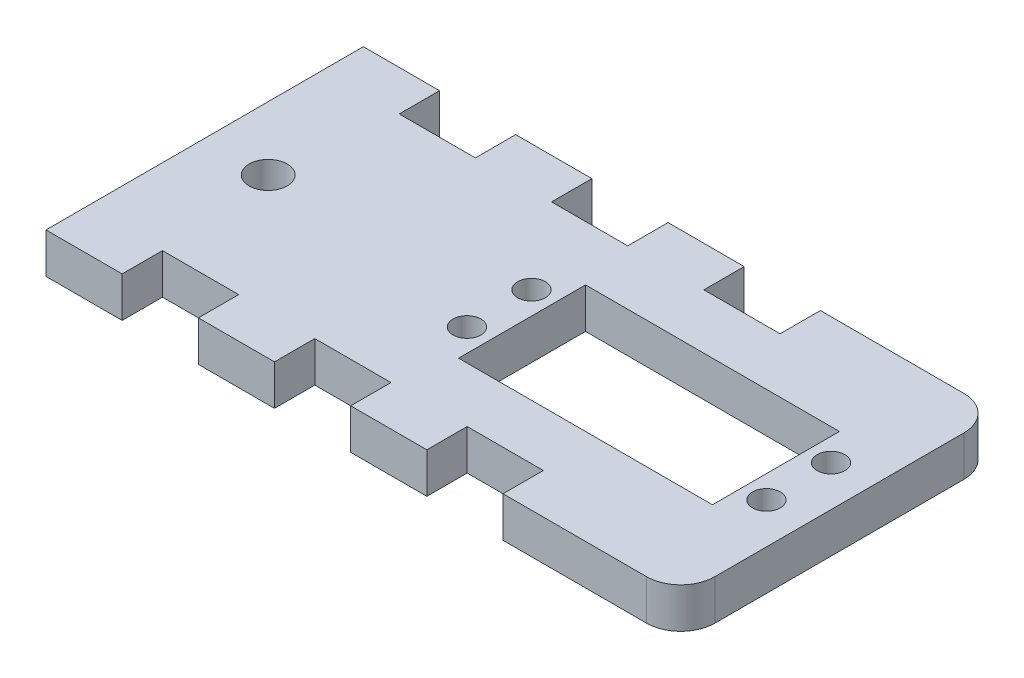
SolidWorks part; units mm, degrees
ref_plane "Front" through (0, 0, 0) normal (0, 0, 1) x (1, 0, 0)
ref_plane "Top" through (0, 0, 0) normal (0, 1, 0) x (1, 0, 0)
ref_plane "Right" through (0, 0, 0) normal (1, 0, 0) x (0, 0, -1)
sketch "Sketch2" plane through (0, 0, 0) normal (0, 1, 0) x (1, 0, 0)
  line L0 (-70, 25) -> (24.62, 25) construction
  line L1 (-20, 10) -> (20, 10)
  line L2 (-20, 10) -> (-20, -10)
  line L3 (-20, -10) -> (20, -10)
  line L4 (20, 10) -> (20, -10)
  line L5 (-20, 10) -> (20, -10) construction
  line L6 (-20, -10) -> (20, 10) construction
  line L7 (-70, 25) -> (-70, -25)
  line L8 (30, 19.62) -> (30, -19.62)
  line L9 (-70, -25) -> (24.62, -25) construction
  line L10 (-70, 25) -> (30, -25) construction
  line L11 (30, 25) -> (-70, -25) construction
  line L12 (-70, 0) -> (30, 0) construction
  line L13 (-23.59, 5.085) -> (-23.59, -5.085) construction
  line L14 (23.59, 5.085) -> (23.59, -5.085) construction
  line L15 (23.59, 0) -> (20, 0) construction
  line L16 (-23.59, 0) -> (-20, 0) construction
  line L17 (-70, 18.65) -> (24.62, 18.65) construction
  line L18 (-70, -18.65) -> (24.62, -18.65) construction
  line L19 (-58, 25) -> (-58, 18.65)
  line L20 (-58, 18.65) -> (-46, 18.65)
  line L21 (-46, 18.65) -> (-46, 25)
  line L22 (-46, 25) -> (-34, 25)
  line L23 (-34, 25) -> (-34, 18.65)
  line L24 (-34, 18.65) -> (-22, 18.65)
  line L25 (-22, 18.65) -> (-22, 25)
  line L26 (-22, 25) -> (-10, 25)
  line L27 (-10, 25) -> (-10, 18.65)
  line L28 (-10, 18.65) -> (2, 18.65)
  line L29 (2, 18.65) -> (2, 25)
  line L30 (-70, 25) -> (-58, 25)
  line L31 (2, 25) -> (24.62, 25)
  line L32 (2, -25) -> (24.62, -25)
  line L33 (2, -18.65) -> (2, -25)
  line L34 (-10, -18.65) -> (2, -18.65)
  line L35 (-10, -25) -> (-10, -18.65)
  line L36 (-22, -25) -> (-10, -25)
  line L37 (-22, -18.65) -> (-22, -25)
  line L38 (-34, -18.65) -> (-22, -18.65)
  line L39 (-34, -25) -> (-34, -18.65)
  line L40 (-46, -25) -> (-34, -25)
  line L41 (-46, -18.65) -> (-46, -25)
  line L42 (-58, -18.65) -> (-46, -18.65)
  line L43 (-58, -25) -> (-58, -18.65)
  line L44 (-70, -25) -> (-58, -25)
  circle A0 centre (23.59, 5.085) radius 2.19
  circle A1 centre (23.59, -5.085) radius 2.19
  circle A2 centre (-23.59, 5.085) radius 2.19
  circle A3 centre (-23.59, -5.085) radius 2.19
  arc A4 (30, -19.62) -> (24.62, -25) centre (24.62, -19.62) cw
  arc A5 (24.62, 25) -> (30, 19.62) centre (24.62, 19.62) cw
  circle A6 centre (-60, 0) radius 3
  point P0 (0, 0)
  point P7 (-20, 0)
  dimension "D6" = 4.38
  dimension "D7" = 10.17
  dimension "D9" = 5.38
  dimension "D10" = 6
  dimension "D1" = 20
  dimension "D2" = 40
  dimension "D3" = 50
  dimension "D4" = 100
  dimension "D5" = 10
  dimension "D8" = 3.59
  dimension "D11" = 10
  dimension "D12" = 6.35
  dimension "D13" = 6.35
  dimension "D14" = 12
  dimension "D15" = 12
extrude "Boss-Extrude2" add sketch "Sketch2" along normal blind 6.35
